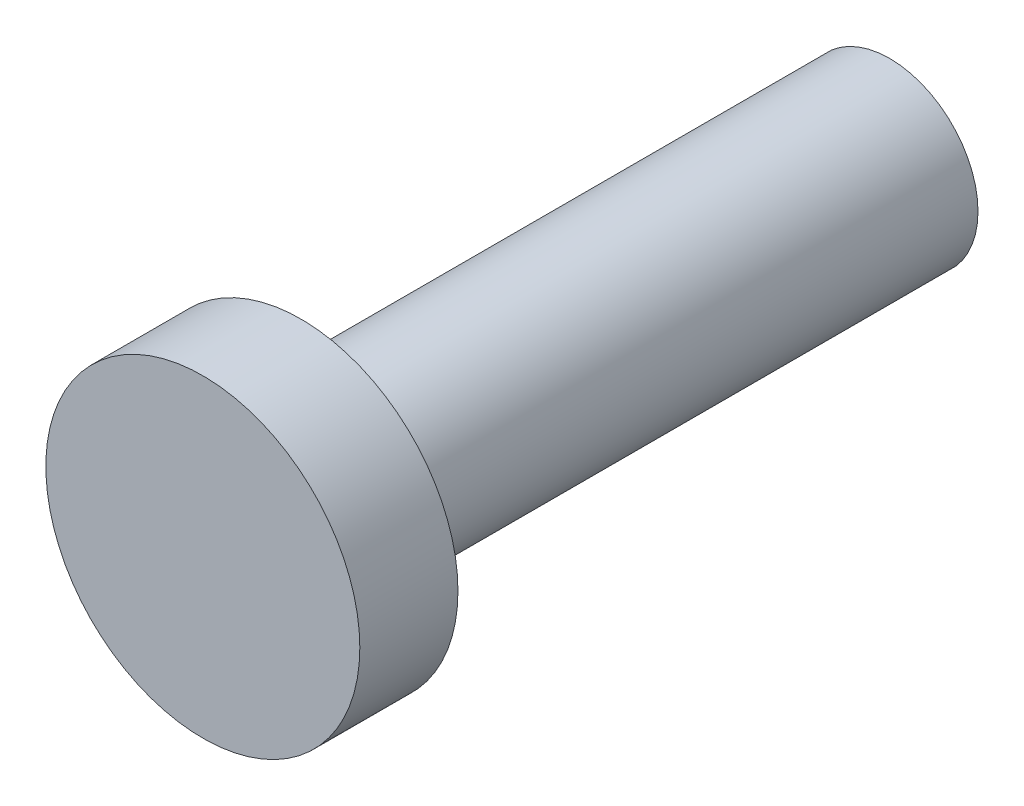
SolidWorks part; units mm, degrees
ref_plane "Plano frontal" through (0, 0, 0) normal (0, 0, 1) x (1, 0, 0)
ref_plane "Plano superior" through (0, 0, 0) normal (0, 1, 0) x (1, 0, 0)
ref_plane "Plano direito" through (0, 0, 0) normal (1, 0, 0) x (0, 0, -1)
sketch "Esboço1" plane through (0, 0, 0) normal (0, 0, 1) x (1, 0, 0)
  circle A0 centre (0, 0) radius 4.5
  dimension "D1" = 9
extrude "Ressalto-extrusão2" add sketch "Esboço1" along normal blind 30 contours A0
sketch "Esboço5" plane through (0, 0, 30) normal (0, 0, 1) x (1, 0, 0)
  circle A0 centre (0, 0) radius 8
  dimension "D1" = 16
extrude "Ressalto-extrusão4" add sketch "Esboço5" along normal blind 5
